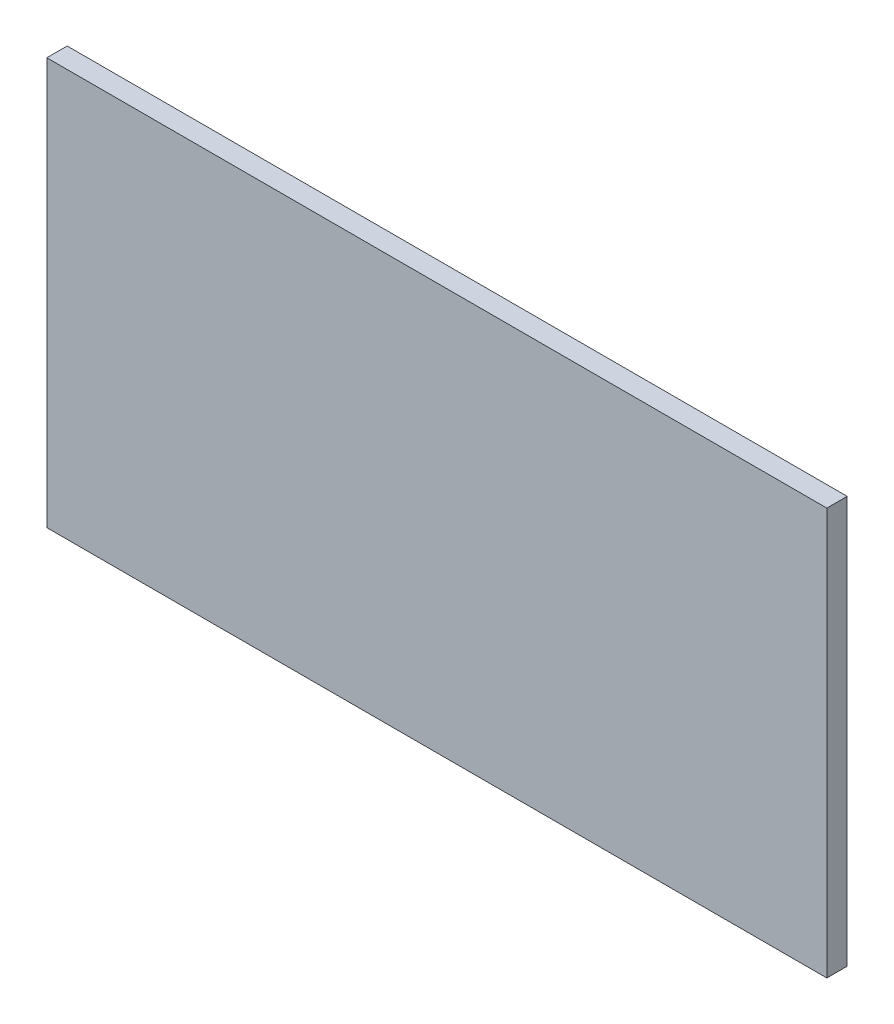
SolidWorks part; units mm, degrees
ref_plane "Plano frontal" through (0, 0, 0) normal (0, 0, 1) x (1, 0, 0)
ref_plane "Plano superior" through (0, 0, 0) normal (0, 1, 0) x (1, 0, 0)
ref_plane "Plano direito" through (0, 0, 0) normal (1, 0, 0) x (0, 0, -1)
sketch "Esboço1" plane through (0, 0, 0) normal (0, 0, 1) x (1, 0, 0)
  line L1 (0, 0) -> (230, 0)
  line L2 (0, 0) -> (0, -120)
  line L3 (0, -120) -> (230, -120)
  line L4 (230, 0) -> (230, -120)
extrude "Ressalto-extrusão1" add sketch "Esboço1" along normal blind 6
